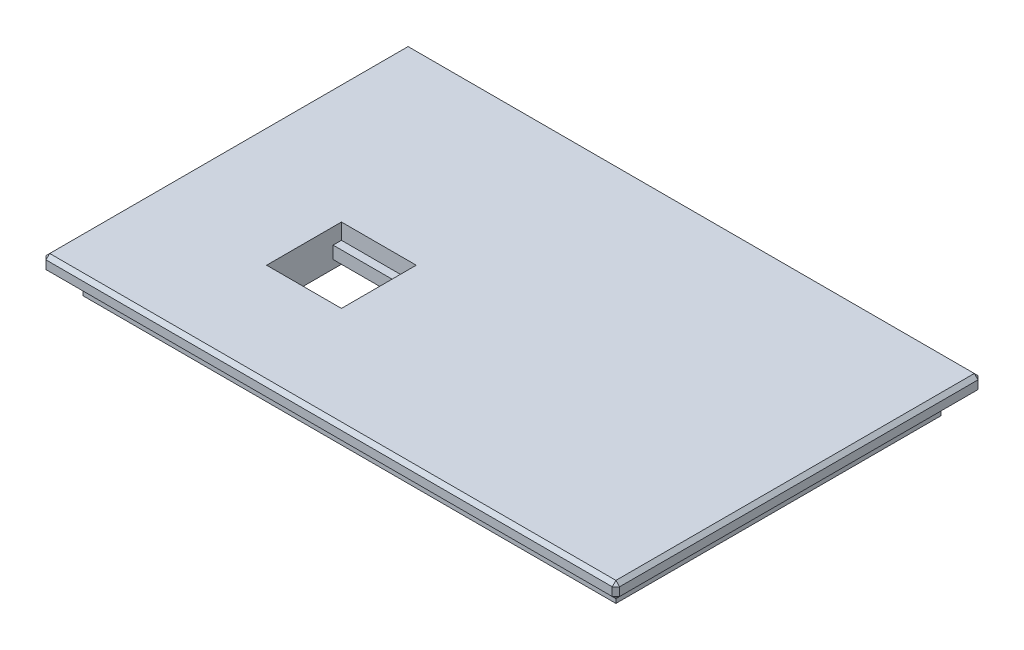
SolidWorks part; units mm, degrees
ref_plane "Front Plane" through (0, 0, 0) normal (0, 0, 1) x (1, 0, 0)
ref_plane "Top Plane" through (0, 0, 0) normal (0, 1, 0) x (1, 0, 0)
ref_plane "Right Plane" through (0, 0, 0) normal (1, 0, 0) x (0, 0, -1)
sketch "Sketch1" plane through (0, 0, 0) normal (0, 1, 0) x (1, 0, 0)
  line L1 (-36.83, -59.806) -> (101.17, -59.806)
  line L2 (-36.83, -59.806) -> (-36.83, 28.194)
  line L3 (-36.83, 28.194) -> (101.17, 28.194)
  line L4 (101.17, -59.806) -> (101.17, 28.194)
  point P0 (0, 0)
  dimension "D1" = 138
  dimension "D2" = 88
extrude "Boss-Extrude1" add sketch "Sketch1" against normal blind 3.81
chamfer "Chamfer1" distance 0.889 angle 45 12 edges at (32.17, -3.81, -28.194) (-36.83, -3.81, 15.806) (-36.83, -1.905, -28.194) (101.17, -1.905, -28.194) (101.17, -3.81, 15.806) (-36.83, 0, 15.806) (32.17, 0, -28.194) (101.17, 0, 15.806) (101.17, -1.905, 59.806) (32.17, -3.81, 59.806) (-36.83, -1.905, 59.806) (32.17, 0, 59.806)
ref_plane "Plane1" through (0, -3.81, 0) normal (0, -1, 0) x (-1, 0, 0)
sketch "Sketch2" plane through (0, -3.81, 0) normal (0, 1, 0) x (1, 0, 0)
  line L0 (-35.941, 27.305) -> (-35.941, -58.917) construction
  line L5 (-31.941, 23.305) -> (96.281, 23.305)
  line L6 (-31.941, 23.305) -> (-31.941, -54.917)
  line L7 (-31.941, -54.917) -> (96.281, -54.917)
  line L8 (96.281, 23.305) -> (96.281, -54.917)
  line L9 (100.281, 27.305) -> (-35.941, 27.305) construction
  line L10 (100.281, -58.917) -> (100.281, 27.305) construction
  line L11 (-35.941, -58.917) -> (100.281, -58.917) construction
  dimension "D1" = 4
  dimension "D2" = 4
  dimension "D3" = 4
  dimension "0.4" = 4
extrude "Boss-Extrude2" add sketch "Sketch2" against normal blind 5 separate body
ref_plane "Plane2" through (0, 0, 0) normal (0, 1, 0) x (1, 0, 0)
sketch "Sketch3" plane through (0, 0, 0) normal (0, -1, 0) x (-1, 0, 0)
  line L0 (-1.5992, -17.2723) -> (-1.5992, -35.2723) construction
  line L1 (7.4008, -35.2723) -> (-10.5992, -35.2723)
  line L2 (7.4008, -35.2723) -> (7.4008, -17.2723)
  line L3 (7.4008, -17.2723) -> (-10.5992, -17.2723)
  line L4 (-10.5992, -35.2723) -> (-10.5992, -17.2723)
  line L5 (7.4008, -26.2723) -> (-11.0657, -26.2723) construction
  point P8 (0, 0)
  dimension "D1" = 18
  dimension "D2" = 18
extrude "Cut-Extrude1" cut sketch "Sketch3" along normal blind 10
sketch "Sketch4" plane through (0, -3.81, 0) normal (0, -1, 0) x (-1, 0, 0)
  line L0 (-10.5992, -35.2723) -> (-10.5992, -17.2723) construction
  line L8 (7.4008, -17.2723) -> (-10.5992, -17.2723)
  line L14 (7.4008, -17.2723) -> (7.4008, -19.2723)
  line L15 (7.4008, -19.2723) -> (-10.5992, -19.2723)
  line L17 (-10.5992, -17.2723) -> (-10.5992, -19.2723)
  line L19 (7.4008, -35.2723) -> (-10.5992, -35.2723)
  line L20 (7.4008, -35.2723) -> (7.4008, -33.2723)
  line L21 (7.4008, -33.2723) -> (-10.5992, -33.2723)
  line L22 (-10.5992, -35.2723) -> (-10.5992, -33.2723)
  dimension "D1" = 2
  dimension "D2" = 2
extrude "Boss-Extrude3" add sketch "Sketch4" along normal blind 3
